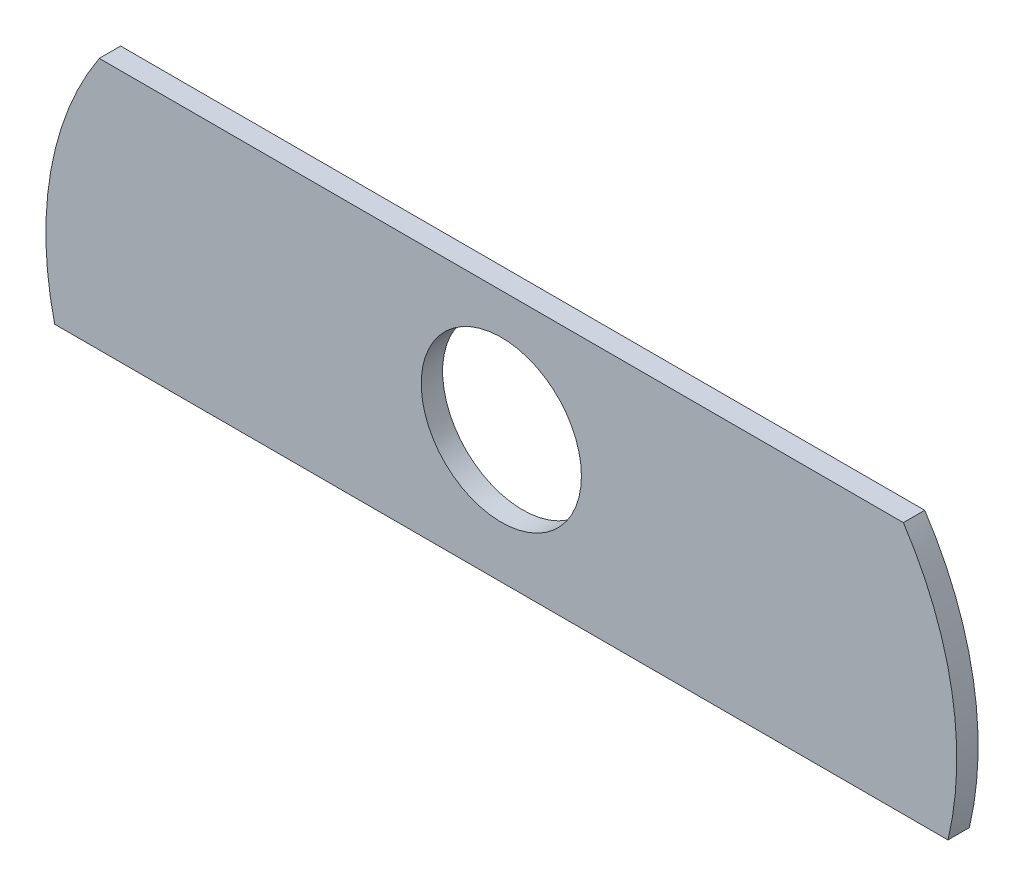
SolidWorks part; units mm, degrees
material "Nylon 101"
ref_plane "Front Plane" through (0, 0, 0) normal (0, 0, 1) x (1, 0, 0)
ref_plane "Top Plane" through (0, 0, 0) normal (0, 1, 0) x (1, 0, 0)
ref_plane "Right Plane" through (0, 0, 0) normal (1, 0, 0) x (0, 0, -1)
sketch "Sketch5" plane through (0, 0, 0) normal (0, 0, 1) x (1, 0, 0)
  line L0 (-37.65, 16.64) -> (37.65, 16.64)
  line L1 (42.65, 16.64) -> (42.65, -16.64) construction
  line L2 (37.65, -16.64) -> (-37.65, -16.64)
  line L3 (-42.65, -16.64) -> (-42.65, 16.64) construction
  line L4 (0, 16.64) -> (0, -16.64) construction
  arc A0 (-37.65, 16.64) -> (-37.65, -16.64) centre (-12.461, 0) ccw
  arc A1 (37.65, 16.64) -> (37.65, -16.64) centre (12.461, 0) cw
  point P4 (9.4665, 22.4823)
  point P13 (-33.1835, 22.4823)
  point P14 (0, 0)
  point P15 (0, 16.64)
  point P16 (0, 0)
  point P17 (0, 0)
  point P18 (0, 0)
  point P19 (0, 0)
  point P20 (0, 0)
  point P21 (-33.1835, 0)
  point P22 (-27.0966, 0)
  point P24 (0, 0)
  point P25 (0, 0)
  dimension "D3" = 30.189
  dimension "D1" = 75.3
  dimension "D2" = 33.28
  dimension "D4" = 5
extrude "Boss-Extrude1" add sketch "Sketch5" along normal blind 2
sketch "Sketch6" plane through (0, 0, 2) normal (0, 0, 1) x (1, 0, 0)
  line L0 (37.65, 16.64) -> (-37.65, 16.64) construction
  circle A0 centre (0, 5.34) radius 7.5
  point P3 (0, 0)
  dimension "D1" = 15
  dimension "D2" = 11.3
extrude "Cut-Extrude1" cut sketch "Sketch6" against normal blind 2
sketch "Sketch7" plane through (0, 0, 2) normal (0, 0, 1) x (1, 0, 0)
  line L1 (-47.6172, -7.0108) -> (48.5583, -7.0108)
  line L2 (-47.6172, -7.0108) -> (-47.6172, -22.6323)
  line L3 (-47.6172, -22.6323) -> (48.5583, -22.6323)
  line L4 (48.5583, -7.0108) -> (48.5583, -22.6323)
  line L5 (-47.6172, -7.0108) -> (48.5583, -22.6323) construction
  line L6 (-47.6172, -22.6323) -> (48.5583, -7.0108) construction
  point P4 (0.4705, -14.8216)
extrude "Cut-Extrude2" cut sketch "Sketch7" against normal blind 2
